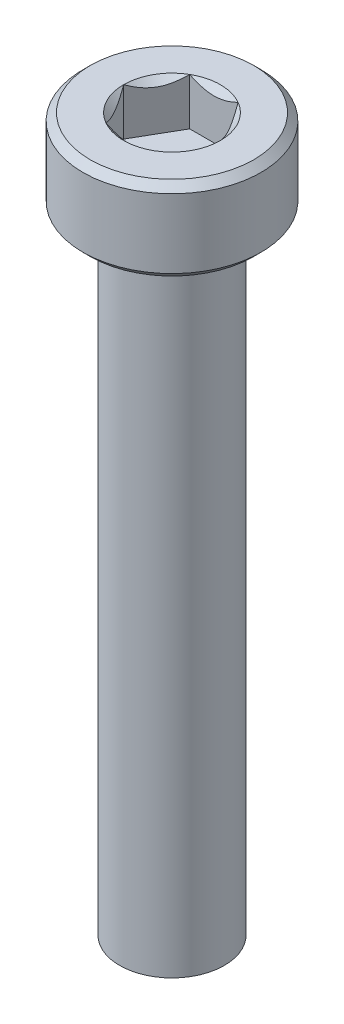
SolidWorks part; units mm, degrees
ref_plane "Front" through (0, 0, 0) normal (0, 0, 1) x (1, 0, 0)
ref_plane "Top" through (0, 0, 0) normal (0, 1, 0) x (1, 0, 0)
ref_plane "Right" through (0, 0, 0) normal (1, 0, 0) x (0, 0, -1)
sketch "Sketch1" plane through (0, 0, 0) normal (0, 1, 0) x (1, 0, 0)
  circle A0 centre (0, 0) radius 4.25
  dimension "D1" = 8.5
extrude "Boss-Extrude1" add sketch "Sketch1" along normal blind 4
sketch "Sketch2" plane through (0, 4, 0) normal (0, 1, 0) x (1, 0, 0)
  line L1 (1.1547, 2) -> (-1.1547, 2)
  line L2 (-1.1547, 2) -> (-2.3094, 0)
  line L3 (-2.3094, 0) -> (-1.1547, -2)
  line L4 (-1.1547, -2) -> (1.1547, -2)
  line L5 (1.1547, -2) -> (2.3094, 0)
  line L6 (2.3094, 0) -> (1.1547, 2)
  circle A0 centre (0, 0) radius 2 construction
  point P10 (0, 2)
  dimension "D1" = 4
extrude "Cut-Extrude1" cut sketch "Sketch2" against normal blind 2.25
sketch "Sketch3" plane through (0, 4, 0) normal (0, 1, 0) x (1, 0, 0)
  circle A0 centre (0, 0) radius 2.3094
extrude "Cut-Extrude2" cut sketch "Sketch3" against normal through all draft 45
chamfer "Chamfer1" distance 0.35 angle 45 2 edges at (0, 0, 4.25) (0, 4, 4.25)
sketch "草图1" plane through (0, 0, 0) normal (0, -1, 0) x (-1, 0, 0)
  circle A0 centre (0, 0) radius 2.5
  dimension "D1" = 5
extrude "凸台-拉伸1" add sketch "草图1" along normal blind 30
